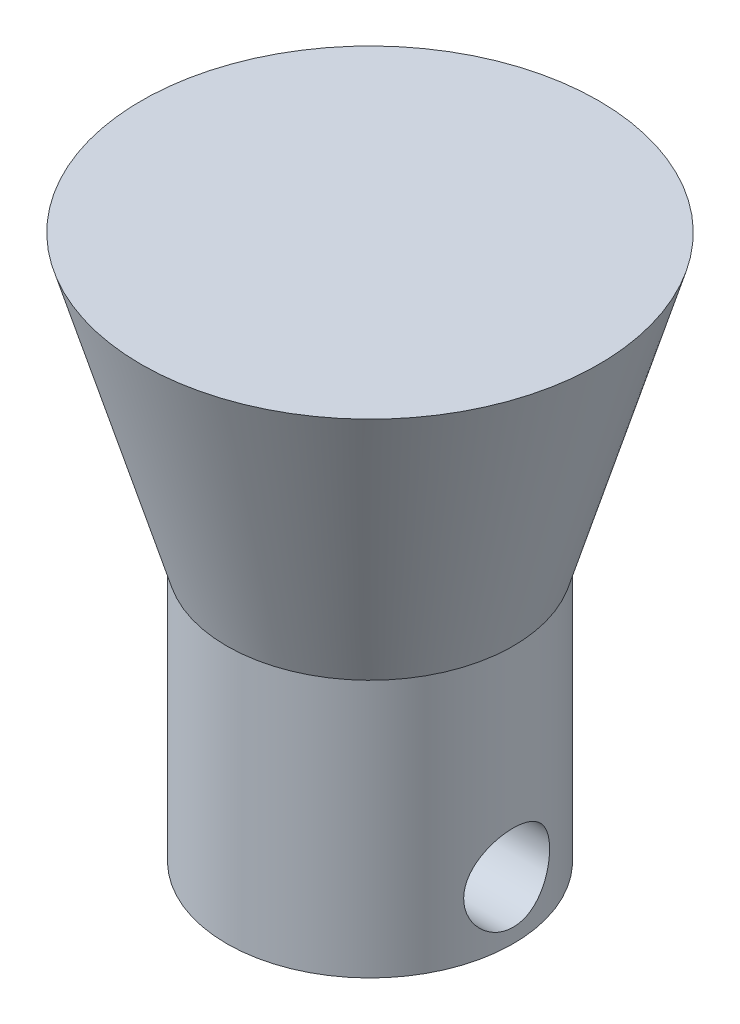
SolidWorks part; units mm, degrees
ref_plane "Front Plane" through (0, 0, 0) normal (0, 0, 1) x (1, 0, 0)
ref_plane "Top Plane" through (0, 0, 0) normal (0, 1, 0) x (1, 0, 0)
ref_plane "Right Plane" through (0, 0, 0) normal (1, 0, 0) x (0, 0, -1)
sketch "Sketch1" plane through (0, 0, 0) normal (0, 1, 0) x (1, 0, 0)
  circle A0 centre (0, 0) radius 5
  dimension "D1" = 10
extrude "body" add sketch "Sketch1" along normal blind 9
sketch "Sketch2" plane through (0, 0, 0) normal (1, 0, 0) x (0, 0, -1)
  circle A0 centre (0, 2) radius 1.5
  dimension "D1" = 2
  dimension "D2" = 3
extrude "pin insert" cut sketch "Sketch2" against normal through all and the other way through all
ref_plane "contact plane" through (0, 19, 0) normal (0, 1, 0) x (1, 0, 0)
sketch "head SA" plane through (0, 19, 0) normal (0, 1, 0) x (1, 0, 0)
  circle A0 centre (0, 0) radius 7.979
  dimension "D1" = 15.958
loft "cone" add profiles "head SA" section "head SA" section face at (0, 9, 5)
